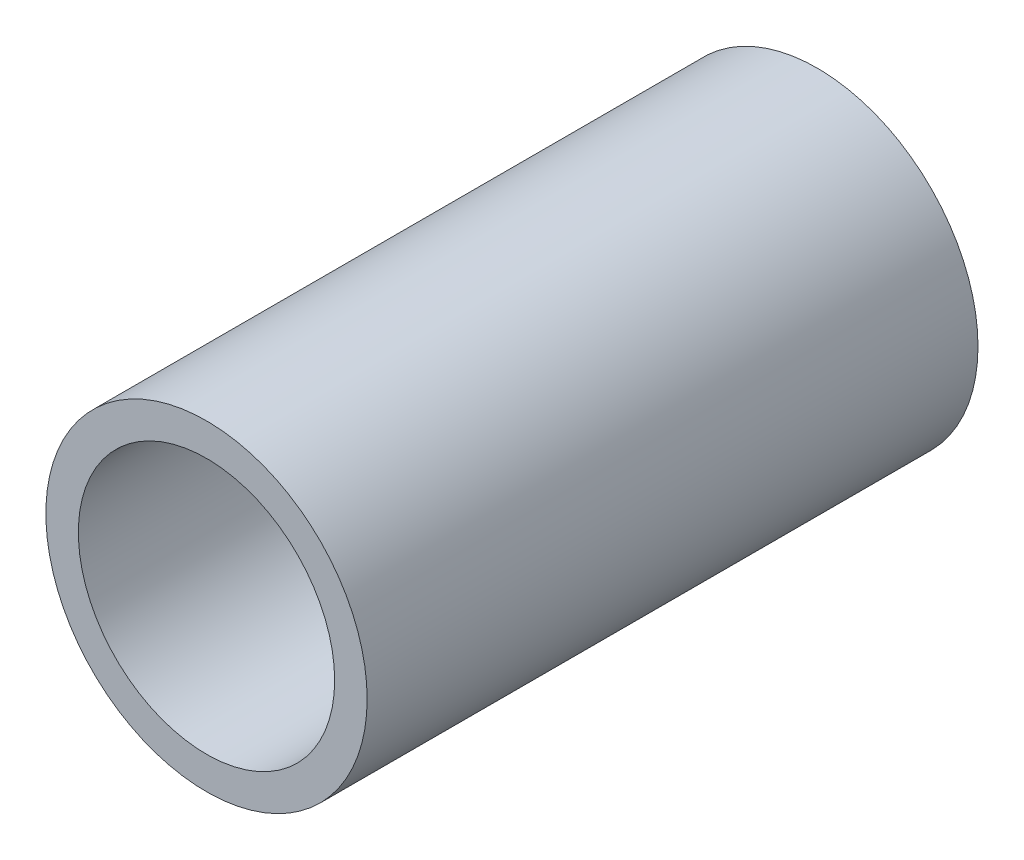
SolidWorks part; units mm, degrees
ref_plane "Front Plane" through (0, 0, 0) normal (0, 0, 1) x (1, 0, 0)
ref_plane "Top Plane" through (0, 0, 0) normal (0, 1, 0) x (1, 0, 0)
ref_plane "Right Plane" through (0, 0, 0) normal (1, 0, 0) x (0, 0, -1)
sketch "Sketch1" plane through (0, 0, 0) normal (0, 0, 1) x (1, 0, 0)
  circle A0 centre (0, 0) radius 16.7005
  dimension "Pipe OD" = 33.401
extrude "Extrude-Thin1" add sketch "Sketch1" along normal mid plane 63.5 thin thin type one direction reverse wall 3.3782
